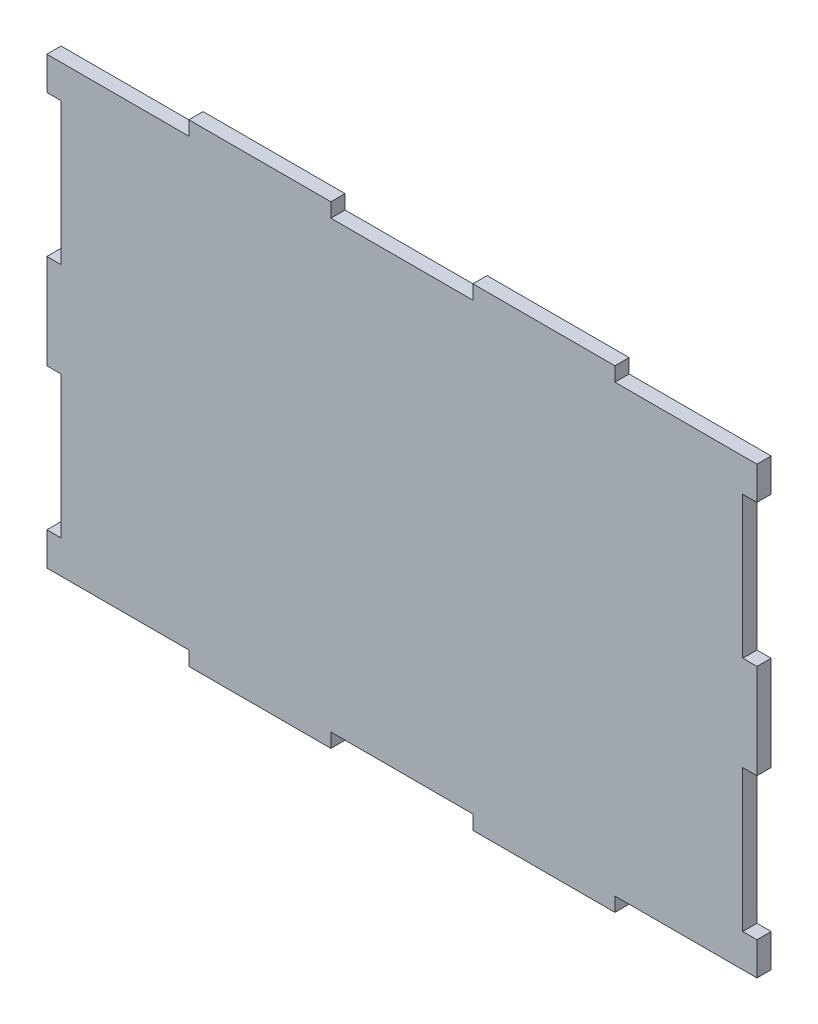
SolidWorks part; units mm, degrees
ref_plane "Plan de face" through (0, 0, 0) normal (0, 0, 1) x (1, 0, 0)
ref_plane "Plan de dessus" through (0, 0, 0) normal (0, 1, 0) x (1, 0, 0)
ref_plane "Plan de droite" through (0, 0, 0) normal (1, 0, 0) x (0, 0, -1)
sketch "Esquisse1" plane through (0, 0, 0) normal (0, 0, 1) x (1, 0, 0)
  line L0 (71.1759, -7.3901) -> (71.1759, -27.3901)
  line L1 (-48.8241, 32.6099) -> (-18.8241, 32.6099)
  line L2 (-78.8241, 32.6099) -> (-78.8241, 22.6099)
  line L3 (-48.8241, -67.3901) -> (-18.8241, -67.3901)
  line L4 (71.1759, 29.6099) -> (71.1759, 22.6099)
  line L5 (71.1759, 22.6099) -> (68.1759, 22.6099)
  line L6 (71.1759, -57.3901) -> (71.1759, -64.3901)
  line L7 (71.1759, -7.3901) -> (68.1759, -7.3901)
  line L8 (68.1759, 22.6099) -> (68.1759, -7.3901)
  line L9 (71.1759, -27.3901) -> (68.1759, -27.3901)
  line L10 (11.1759, -67.3901) -> (41.1759, -67.3901)
  line L11 (71.1759, -57.3901) -> (68.1759, -57.3901)
  line L12 (68.1759, -27.3901) -> (68.1759, -57.3901)
  line L13 (-78.8241, 22.6099) -> (-75.8241, 22.6099)
  line L14 (-78.8241, -57.3901) -> (-78.8241, -67.3901)
  line L15 (-78.8241, -7.3901) -> (-75.8241, -7.3901)
  line L16 (-75.8241, 22.6099) -> (-75.8241, -7.3901)
  line L17 (-78.8241, -27.3901) -> (-75.8241, -27.3901)
  line L19 (-78.8241, -57.3901) -> (-75.8241, -57.3901)
  line L20 (-75.8241, -27.3901) -> (-75.8241, -57.3901)
  line L21 (11.1759, 32.6099) -> (41.1759, 32.6099)
  line L22 (-78.8241, -67.3901) -> (-78.8241, -64.3901)
  line L23 (-78.8241, -64.3901) -> (-48.8241, -64.3901)
  line L24 (-48.8241, -67.3901) -> (-48.8241, -64.3901)
  line L25 (-78.8241, -7.3901) -> (-78.8241, -27.3901)
  line L27 (71.1759, -64.3901) -> (41.1759, -64.3901)
  line L28 (41.1759, -67.3901) -> (41.1759, -64.3901)
  line L30 (11.1759, -67.3901) -> (11.1759, -64.3901)
  line L31 (11.1759, -64.3901) -> (-18.8241, -64.3901)
  line L32 (-18.8241, -67.3901) -> (-18.8241, -64.3901)
  line L34 (-78.8241, 32.6099) -> (-78.8241, 29.6099)
  line L35 (-78.8241, 29.6099) -> (-48.8241, 29.6099)
  line L36 (-48.8241, 32.6099) -> (-48.8241, 29.6099)
  line L38 (-18.8241, 32.6099) -> (-18.8241, 29.6099)
  line L39 (-18.8241, 29.6099) -> (11.1759, 29.6099)
  line L40 (11.1759, 32.6099) -> (11.1759, 29.6099)
  line L43 (71.1759, 29.6099) -> (41.1759, 29.6099)
  line L44 (41.1759, 32.6099) -> (41.1759, 29.6099)
  dimension "D3" = 3
  dimension "D4" = 3
  dimension "D5" = 10
  dimension "D6" = 10
  dimension "D7" = 30
  dimension "D8" = 30
  dimension "D9" = 3
  dimension "D10" = 3
  dimension "D11" = 30
  dimension "D12" = 30
  dimension "D13" = 10
  dimension "D14" = 10
  dimension "D15" = 30
  dimension "D16" = 3
  dimension "D17" = 3
  dimension "D18" = 3
  dimension "D19" = 3
  dimension "D20" = 3
  dimension "D21" = 3
  dimension "D22" = 30
  dimension "D23" = 30
  dimension "D24" = 30
  dimension "D25" = 30
  dimension "D26" = 30
  dimension "D27" = 30
  dimension "D28" = 30
  dimension "D29" = 10
extrude "Boss.-Extru.1" add sketch "Esquisse1" along normal blind 3 contours L44 L21 L40 L39 L38 L1 L36 L35 L2 L13 L16 L15 L25 L17 L20 L19 L14 L23 L24 L3 L32 L31 L30 L10 L28 L27 L6 L11 L12 L9 L0 L7 L8 L5 L4 L43
